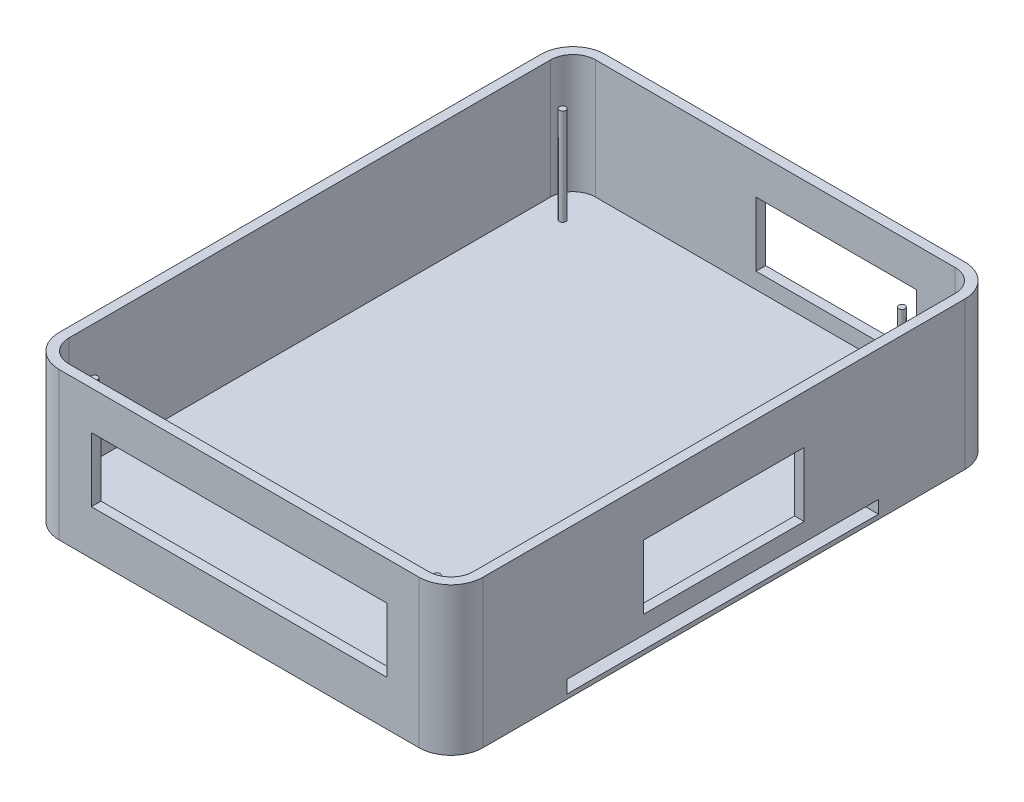
SolidWorks part; units mm, degrees
other "Annotazione5"
sketch "Schizzo12" plane through (64, 40, 0) normal (0.5774, 0.5773, 0.5774) x (0.7071, 0, -0.7071)
other "ElementoDettaglio5"
ref_plane "Piano frontale" through (0, 0, 0) normal (0, 0, 1) x (1, 0, 0)
ref_plane "Piano superiore" through (0, 0, 0) normal (0, 1, 0) x (1, 0, 0)
ref_plane "Piano destro" through (0, 0, 0) normal (1, 0, 0) x (0, 0, -1)
sketch "Schizzo1" plane through (0, 0, 0) normal (0, 1, 0) x (1, 0, 0)
  line L1 (0, 0) -> (66, 0)
  line L2 (0, 0) -> (0, 85)
  line L3 (0, 85) -> (66, 85)
  line L4 (66, 0) -> (66, 85)
  dimension "D1" = 66
  dimension "D2" = 85
extrude "Estrusione-Estrusione1" add sketch "Schizzo1" along normal blind 20
fillet "Raccordo1" radius 5 2 edges at (66, 10, 0) (0, 10, 0)
fillet "Raccordo2" radius 5 1 edges at (66, 10, -85)
fillet "Raccordo3" radius 5 1 edges at (0, 10, -85)
shell "Svuota2" thickness 1.5
sketch "Schizzo3" plane through (0, 1.5, 0) normal (0, 1, 0) x (1, 0, 0)
  line L0 (5, 1.5) -> (61, 1.5) construction
  line L1 (61.375, 2.96) -> (2.965, 2.96)
  line L2 (61.375, 2.96) -> (61.375, 80.43)
  line L3 (61.375, 80.43) -> (2.965, 80.43)
  line L4 (2.965, 2.96) -> (2.965, 80.43)
  line L5 (61.375, 2.96) -> (2.965, 80.43) construction
  line L6 (61.375, 80.43) -> (2.965, 2.96) construction
  line L7 (58.84, 5.5) -> (5.5, 5.5)
  line L8 (58.84, 5.5) -> (58.84, 77.89)
  line L9 (58.84, 77.89) -> (5.5, 77.89)
  line L10 (5.5, 5.5) -> (5.5, 77.89)
  line L11 (58.84, 5.5) -> (5.5, 77.89) construction
  line L12 (58.84, 77.89) -> (5.5, 5.5) construction
  line L14 (1.5, 80) -> (1.5, 5) construction
  circle A0 centre (5.5, 77.89) radius 0.5
  point P0 (32.17, 41.695)
  point P6 (32.17, 41.695)
  dimension "D5" = 1
  dimension "D1" = 58.41
  dimension "D2" = 77.47
  dimension "D3" = 53.34
  dimension "D4" = 72.39
  dimension "D6" = 4
  dimension "D7" = 4
extrude "Estrusione-Estrusione2" add sketch "Schizzo3" along normal blind 15 contours A0
sketch "Schizzo6" plane through (0, 1.5, 0) normal (0, 1, 0) x (1, 0, 0)
  circle A0 centre (58.665, 77.536) radius 0.5
  circle A1 centre (58.665, 5.1328) radius 0.5
  circle A2 centre (5.3457, 5.1328) radius 0.5
  dimension "D1" = 1
  dimension "D2" = 1
  dimension "D3" = 1
extrude "Estrusione-Estrusione3" add sketch "Schizzo6" along normal blind 15
sketch "Schizzo13" plane through (0, 0, -85) normal (0, 0, -1) x (-1, 0, 0)
  line L0 (-61, 0) -> (-5, 0) construction
  line L1 (-30, 4) -> (-55, 4)
  line L2 (-30, 4) -> (-30, 14)
  line L3 (-30, 14) -> (-55, 14)
  line L4 (-55, 4) -> (-55, 14)
  line L5 (-30, 4) -> (-55, 14) construction
  line L6 (-30, 14) -> (-55, 4) construction
  line L7 (-5, 0) -> (-5, 20) construction
  point P0 (-42.5, 9)
  dimension "D1" = 4
  dimension "D2" = 25
  dimension "D3" = 25
  dimension "D4" = 10
extrude "Taglio-Estrusione2" cut sketch "Schizzo13" against normal blind 2
sketch "Schizzo18" plane through (0, 0, 0) normal (-1, 0, 0) x (0, 0, 1)
  line L0 (-80, 0) -> (-5, 0) construction
  line L1 (-18.0492, -2.3) -> (-66.5668, -2.3)
  line L2 (-18.0492, -2.3) -> (-18.0492, -0.3)
  line L3 (-18.0492, -0.3) -> (-66.5668, -0.3)
  line L4 (-66.5668, -2.3) -> (-66.5668, -0.3)
  line L5 (-18.0492, -2.3) -> (-66.5668, -0.3) construction
  line L6 (-18.0492, -0.3) -> (-66.5668, -2.3) construction
  line L7 (-5, 0) -> (-5, 20) construction
  point P0 (-42.308, -1.3)
  dimension "D1" = 48.5176
  dimension "D2" = 2
  dimension "D3" = 0.3
  dimension "D4" = 13.0492
sketch "Schizzo19" plane through (0, 0, 0) normal (0, 0, 1) x (1, 0, 0)
  line L0 (5, 0) -> (61, 0) construction
  line L1 (56, 14) -> (10, 14)
  line L2 (56, 14) -> (56, 4)
  line L3 (56, 4) -> (10, 4)
  line L4 (10, 14) -> (10, 4)
  line L5 (56, 14) -> (10, 4) construction
  line L6 (56, 4) -> (10, 14) construction
  line L7 (61, 0) -> (61, 20) construction
  point P0 (33, 9)
  dimension "D1" = 10
  dimension "D2" = 46
  dimension "D3" = 4
  dimension "D4" = 5
extrude "Taglio-Estrusione5" cut sketch "Schizzo19" against normal blind 2
sketch "Schizzo21" plane through (0, 0, 0) normal (0, -1, 0) x (1, 0, 0)
  line L1 (5, 0) -> (61, 0)
  line L2 (0, -5) -> (0, -80)
  line L3 (5, -85) -> (61, -85)
  line L4 (66, -5) -> (66, -80)
  arc A0 (0, -5) -> (5, 0) centre (5, -5) cw
  arc A1 (66, -5) -> (61, 0) centre (61, -5) ccw
  arc A2 (61, -85) -> (66, -80) centre (61, -80) ccw
  arc A3 (0, -80) -> (5, -85) centre (5, -80) ccw
  point P7 (0, 0)
  point P10 (66, 0)
  point P13 (66, -85)
  dimension "D3" = 5
  dimension "D4" = 5
  dimension "D5" = 5
  dimension "D6" = 5
  dimension "D1" = 85
  dimension "D2" = 66
extrude "Estrusione-Estrusione4" add sketch "Schizzo21" along normal blind 3
extrude "Taglio-Estrusione6" cut sketch "Schizzo18" against normal blind 80
sketch "Schizzo22" plane through (66, 0, 0) normal (1, 0, 0) x (0, 0, -1)
  line L0 (5, 1.5) -> (80, 1.5) construction
  line L1 (55, 12.5) -> (30, 12.5)
  line L2 (55, 12.5) -> (55, 2.5)
  line L3 (55, 2.5) -> (30, 2.5)
  line L4 (30, 12.5) -> (30, 2.5)
  line L5 (55, 12.5) -> (30, 2.5) construction
  line L6 (55, 2.5) -> (30, 12.5) construction
  line L7 (5, 20) -> (5, -3) construction
  point P0 (42.5, 7.5)
  dimension "D1" = 10
  dimension "D2" = 1
  dimension "D3" = 25
  dimension "D4" = 25
extrude "Taglio-Estrusione7" cut sketch "Schizzo22" against normal blind 2
